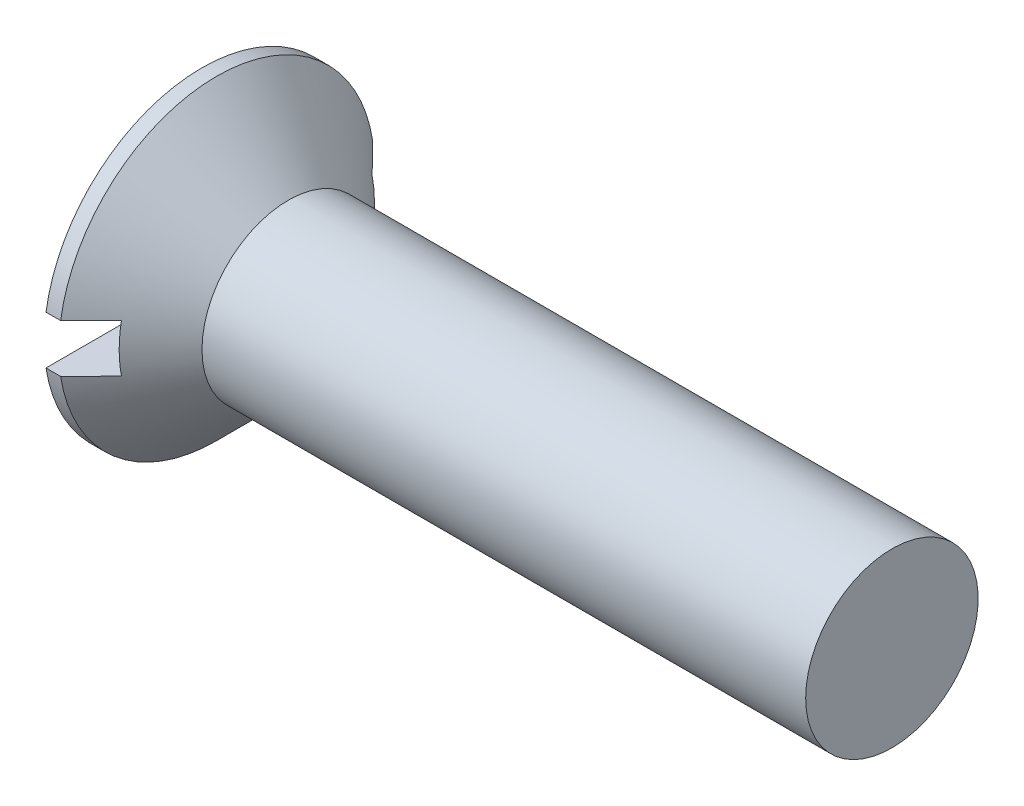
SolidWorks part; units mm, degrees
revolve "Base-Revolve" add sketch "BodySke" angle 360 about L5
sketch "BodySke" plane through (0, 0, 0) normal (0, 0, 1) x (1, 0, 0)
  line L0 (0, 0) -> (0, 9.15)
  line L1 (0, 9.15) -> (0.85, 9.15)
  line L2 (5, 5) -> (40, 5)
  line L3 (40, 5) -> (40, 0)
  line L4 (40, 0) -> (0, 0)
  line L5 (-6.35, 0) -> (82.55, 0) construction
  line L6 (5, -5) -> (40, -5) construction
  line L7 (0.85, -9.15) -> (5, -5) construction
  line L8 (0.85, 9.15) -> (5, 5)
  line L9 (0, -9.15) -> (0.85, -9.15) construction
  line L10 (6.5, 6.5875) -> (6.5, -2.9375) construction
  line L11 (5, 6.35) -> (5, -3.175) construction
  dimension "Head_ang" = 90
cosmetic thread "ThreadCosmetic" [suppressed] parameters "Thread_length"=14.4, "Thread_minor"=8.344
extrude "Slot" cut sketch "Sketch2" against normal blind 2.6
sketch "Sketch2" plane through (0, 0, 0) normal (-1, 0, 0) x (0, 0, 1)
  line L0 (-9.15, -1.4) -> (9.15, -1.4)
  line L1 (-9.15, -1.4) -> (-9.15, 1.4)
  line L2 (9.15, 1.4) -> (-9.15, 1.4)
  line L3 (9.15, 1.4) -> (9.15, -1.4)
  dimension "D1" = 0.35
  dimension "D2" = 3.8
  dimension "D3" = 1.9
ref_plane "Plane1" through (0, 0, 0) normal (0, 0, 1) x (1, 0, 0)
ref_plane "Plane2" through (0, 0, 0) normal (0, 1, 0) x (1, 0, 0)
ref_plane "Plane3" through (0, 0, 0) normal (1, 0, 0) x (0, 0, -1)
sketch "Sketch3" plane through (0, 0, 0) normal (-1, 0, 0) x (0, 0, 1)
  line L0 (-0.99, 4.94) -> (0.99, 4.94)
  line L1 (0.99, 4.94) -> (0.99, -4.94)
  line L2 (0.99, -4.94) -> (-0.99, -4.94)
  line L3 (-0.99, -4.94) -> (-0.99, 4.94)
  dimension "D1" = 1.07
  dimension "D2" = 0.265
ref_plane "Plane4" through (5.98, 0, 0) normal (-1, 0, 0) x (0, 0, 1)
sketch "Sketch4" plane through (5.98, 0, 0) normal (-1, 0, 0) x (0, 0, 1)
  line L0 (-0.495, 0.495) -> (0.495, 0.495)
  line L3 (0.495, 0.495) -> (0.495, -0.495)
  line L4 (0.495, -0.495) -> (-0.495, -0.495)
  line L5 (-0.495, -0.495) -> (-0.495, 0.495)
  dimension "D2" = 0.265
  dimension "D1" = 0.265
  dimension "D3" = 0.1325
  dimension "D4" = 0.1325
loft "Cross" cut profiles "Sketch3", "Sketch4"
pattern_circular "CirPattern1" count 2 every 90 about axis through (0, 0, 0) along (1, 0, 0) of "Cross"
sketch "ThdSchSke" plane through (0, 0, 0) normal (0, 0, 1) x (1, 0, 0)
  line L0 (6.5, -4.172) -> (5.9202, -5)
  line L1 (6.5, -4.172) -> (7.0798, -5)
  line L2 (7.0798, -5) -> (7.0798, -6.25)
  line L3 (-3.175, 0) -> (5.1513, 0) construction
  line L5 (7.0798, -6.25) -> (5.9202, -6.25)
  line L6 (5.9202, -6.25) -> (5.9202, -5)
  line L7 (0, 9.15) -> (0, 1.4) construction
  dimension "Thread_minor" = 1.548
  dimension "Diameter" = 2
  dimension "Start" = 1.6
revolve "ThreadSchematic" [suppressed] cut sketch "ThdSchSke" angle 360 about L3
pattern_linear "ThdSchPat" [suppressed]
equation "\"D1@Sketch3\" = \"Cross_dia@Sketch3\" / 2"
equation "\"D2@Sketch3\" = \"Cross_width@Sketch3\" / 2"
equation "\"D1@Sketch4\" = \"Cross_width@Sketch3\" *.5"
equation "\"D2@Sketch4\" = \"D1@Sketch4\""
equation "\"D4@Sketch4\" = \"D2@Sketch4\" / 2"
equation "\"D3@Sketch4\" = \"D1@Sketch4\" / 2"
equation "\"D1@Sketch2\" = \"Slot_width@Sketch2\" / 2"
equation "\"D2@Sketch2\" = \"Head_dia@BodySke\""
equation "\"D3@Sketch2\" = \"D2@Sketch2\" / 2"
equation "\"Thread_length@ThreadCosmetic\" = ((sgn( (\"Length@BodySke\" - \"Advance@BodySke\" - \"Head_ht@BodySke\" ) - \"Thread_nom@BodySke\" )-1)*( (\"Length@BodySke\" - \"Advance@BodySke\" - \"Head_ht@BodySke\" ) - \"Thread_nom@BodySke\" ))/-2+ \"Thread_nom@BodySke\""
equation "\"Thread_minor@ThdSchSke\" = \"Thread_minor@ThreadCosmetic\""
equation "\"Diameter@ThdSchSke\" = \"Diameter@BodySke\""
equation "\"Overcut@ThdSchSke\" = \"Diameter@BodySke\" * 1.25"
equation "\"Start@ThdSchSke\" = 0.000001 + \"Length@BodySke\" - \"Thread_length@ThreadCosmetic\"  '---Countersunk---"
equation "\"Num_threads@ThdSchPat\" = int( \"Thread_length@ThreadCosmetic\" / \"Advance@BodySke\" + 0.999 )  + 1"
equation "\"Advance@ThdSchPat\" = \"Thread_length@ThreadCosmetic\" /  (\"Num_threads@ThdSchPat\" - 1) 'relax it"
